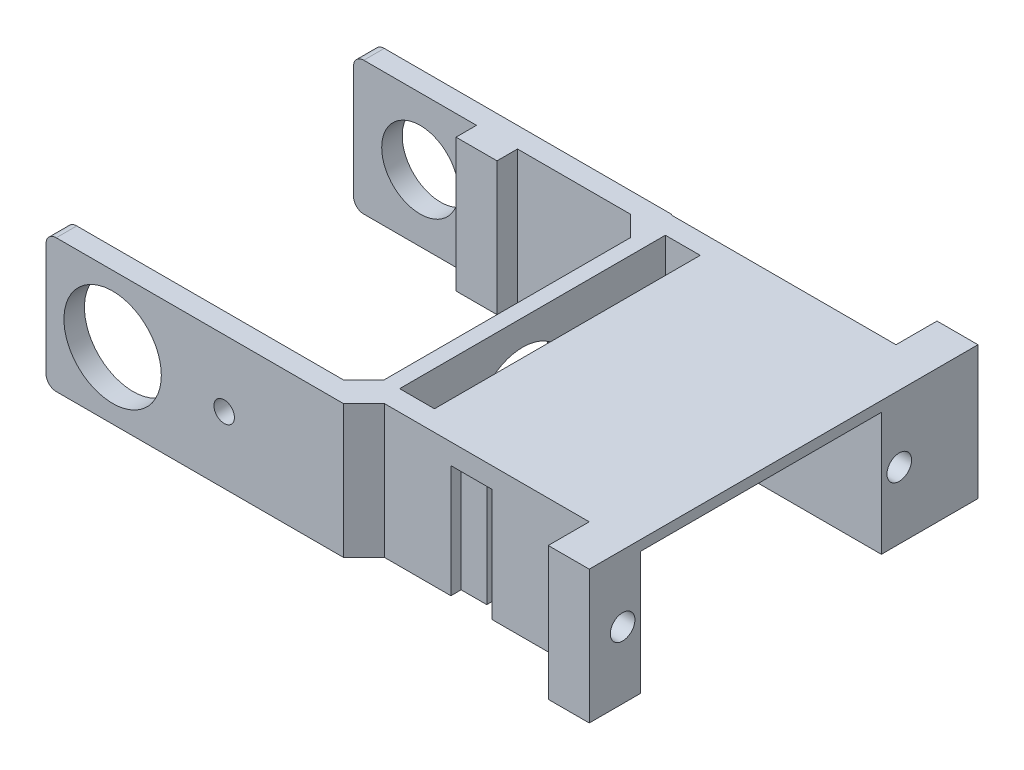
SolidWorks part; units mm, degrees
material "Plain Carbon Steel"
ref_plane "Front Plane" through (0, 0, 0) normal (0, 0, 1) x (1, 0, 0)
ref_plane "Top Plane" through (0, 0, 0) normal (0, 1, 0) x (1, 0, 0)
ref_plane "Right Plane" through (0, 0, 0) normal (1, 0, 0) x (0, 0, -1)
sketch "Sketch1" plane through (0, 0, 0) normal (0, 1, 0) x (1, 0, 0)
  line L0 (-0.069, 0) -> (0.0119, 0) construction
  line L13 (0, 70) -> (0, -70)
  line L14 (0, 70) -> (-10, 80)
  line L15 (-10, 80) -> (-155, 80)
  line L16 (-155, 80) -> (-155, 70)
  line L17 (-155, 70) -> (-20, 70)
  line L18 (-20, 70) -> (-10, 60)
  line L19 (-10, 60) -> (-10, -60)
  line L20 (-10, -60) -> (-20, -70)
  line L21 (-20, -70) -> (-155, -70)
  line L22 (0, -70) -> (-10, -80)
  line L23 (-10, -80) -> (-155, -80)
  line L24 (-155, -80) -> (-155, -70)
  point P6 (0, 0)
  dimension "D1" = 135
  dimension "D2" = 10
  dimension "D3" = 10
  dimension "D4" = 10
  dimension "D5" = 135
  dimension "D6" = 70
extrude "Boss-Extrude1" add sketch "Sketch1" along normal blind 65
fillet "Fillet1" radius 5 4 edges at (-155, 0, 75) (-155, 65, 75) (-155, 65, -75) (-155, 0, -75)
sketch "Sketch2" plane through (0, 0, 0) normal (0, 0, 1) x (1, 0, 0)
  line L0 (-150, 65) -> (-10, 65) construction
  line L1 (-155, 60) -> (-155, 5) construction
  circle A0 centre (-122.5, 32.5) radius 18.75
  dimension "D1" = 37.5
  dimension "D2" = 32.5
  dimension "D3" = 32.5
extrude "Cut-Extrude1" cut sketch "Sketch2" against normal up to surface (80 mm away) up to face at (-105.3452, 32.5, -80)
sketch "Sketch3" plane through (0, 0, 80) normal (0, 0, 1) x (1, 0, 0)
  line L0 (-155, 60) -> (-155, 5) construction
  line L1 (-150, 65) -> (-10, 65) construction
  circle A0 centre (-122.5, 32.5) radius 23.75
  dimension "D1" = 47.5
  dimension "D2" = 32.5
  dimension "D3" = 32.5
extrude "Cut-Extrude2" cut sketch "Sketch3" against normal up to surface (10 mm away) up to face at (-108.6785, 32.5, 70)
sketch "Sketch4" plane through (0, 0, 0) normal (0, 1, 0) x (1, 0, 0)
  line L0 (-9.6326, 79.6326) -> (120, 79.6326)
  line L1 (-10, 60) -> (-10, -60) construction
  line L4 (0, 70) -> (-10, 80) construction
  line L5 (120, 79.6326) -> (120, -70)
  line L6 (0, -70) -> (120, -70)
  line L7 (0, -70) -> (0, 70)
  line L8 (-9.6326, 79.6326) -> (0, 70)
  dimension "D1" = 130
  dimension "D2" = 149.6326
extrude "Boss-Extrude2" add sketch "Sketch4" along normal up to surface (65 mm away) contours L6 L5 L0 L8 L7 up to face at (-56.6667, 65, 0)
sketch "Sketch5" plane through (0, 0, 0) normal (0, -1, 0) x (1, 0, 0)
  line L0 (120, -4.8163) -> (-170.7058, -4.8163) construction
  line L1 (120, -79.6326) -> (120, 70) construction
  line L2 (-10, -60) -> (-10, 60) construction
  line L3 (-2.5, 60) -> (14.5, 60)
  line L4 (-2.5, 60) -> (-2.5, -69.6326)
  line L5 (-2.5, -69.6326) -> (14.5, -69.6326)
  line L6 (14.5, 60) -> (14.5, -69.6326)
  line L7 (-2.5, 60) -> (14.5, -69.6326) construction
  line L8 (-2.5, -69.6326) -> (14.5, 60) construction
  point P4 (6, -4.8163)
  dimension "D1" = 17
  dimension "D2" = 10
  dimension "D3" = 7.5
extrude "Cut-Extrude3" cut sketch "Sketch5" against normal up to surface (65 mm away) up to face at (-32.1166, 65, -1.3761)
sketch "Sketch6" plane through (0, 0, 0) normal (0, -1, 0) x (1, 0, 0)
  line L0 (0, 70) -> (120, 70) construction
  line L5 (120, -79.6326) -> (120, 70) construction
  line L6 (120, 65) -> (45, 65)
  line L7 (120, 65) -> (120, -52.5)
  line L8 (120, -52.5) -> (45, -52.5)
  line L9 (45, 65) -> (45, -52.5)
  dimension "D1" = 75
  dimension "D2" = 5
  dimension "D3" = 117.5
extrude "Cut-Extrude4" cut sketch "Sketch6" against normal blind 60
sketch "Sketch7" plane through (120, 0, 0) normal (1, 0, 0) x (0, 0, -1)
  line L0 (-80, 0) -> (-70, 0) construction
  line L1 (-70, 65) -> (-90, 65)
  line L2 (-70, 65) -> (-70, 0)
  line L3 (-70, 0) -> (-90, 0)
  line L4 (-90, 65) -> (-90, 0)
  line L5 (79.6326, 0) -> (52.5, 0) construction
  line L6 (79.6326, 65) -> (99.6326, 65)
  line L7 (79.6326, 65) -> (79.6326, 0)
  line L8 (79.6326, 0) -> (99.6326, 0)
  line L9 (99.6326, 65) -> (99.6326, 0)
  dimension "D1" = 20
  dimension "D2" = 20
extrude "Boss-Extrude3" add sketch "Sketch7" against normal blind 20
sketch "Sketch8" plane through (120, 0, 0) normal (1, 0, 0) x (0, 0, -1)
  line L3 (99.6326, 65) -> (-90, 65) construction
  line L4 (-6.25, 60) -> (-6.25, -23.4656) construction
  line L5 (52.5, 60) -> (-65, 60) construction
  circle A1 centre (-73.725, 32.5) radius 6
  circle A2 centre (61.225, 32.5) radius 6
  dimension "D1" = 12
  dimension "D4" = 12
  dimension "D5" = 134.95
  dimension "D6" = 32.5
extrude "Cut-Extrude6" cut sketch "Sketch8" against normal blind 20
sketch "Sketch9" plane through (0, 0, 70) normal (0, 0, 1) x (1, 0, 0)
  line L0 (0, 0) -> (100, 0) construction
  line L1 (32.5, 0) -> (52.5, 0)
  line L2 (32.5, 0) -> (32.5, 55)
  line L3 (32.5, 55) -> (52.5, 55)
  line L4 (52.5, 0) -> (52.5, 55)
  dimension "D1" = 20
  dimension "D2" = 55
  dimension "D3" = 32.5
extrude "Cut-Extrude8" cut sketch "Sketch9" against normal up to surface (5 mm away) up to face at (82.5, 30, 65)
sketch "Sketch10" plane through (-10, 0, 0) normal (-1, 0, 0) x (0, 0, 1)
  line L0 (-60, 0) -> (60, 0) construction
  line L1 (-60, 65) -> (-60, 0) construction
  circle A0 centre (0, 30) radius 22.5
  dimension "D1" = 45
  dimension "D2" = 30
  dimension "D3" = 60
extrude "Cut-Extrude9" cut sketch "Sketch10" against normal up to surface (7.5 mm away) up to face at (-2.5, 32.5, -4.8163)
sketch "Sketch11" plane through (0, 0, 0) normal (0, 1, 0) x (1, 0, 0)
  line L0 (-150, 70) -> (-20, 70) construction
  line L1 (-95, 70) -> (-75, 70)
  line L2 (-95, 70) -> (-95, 60)
  line L3 (-95, 60) -> (-75, 60)
  line L4 (-75, 70) -> (-75, 60)
  line L5 (-10, 60) -> (-10, -60) construction
  dimension "D1" = 20
  dimension "D2" = 10
  dimension "D3" = 85
extrude "Boss-Extrude4" add sketch "Sketch11" along normal up to surface (65 mm away) up to face at (6, 65, -4.8163)
sketch "Sketch12" plane through (0, 0, 80) normal (0, 0, 1) x (1, 0, 0)
  line L0 (-150, 65) -> (-10, 65) construction
  circle A0 centre (-68.08, 32.5) radius 5
  circle A1 centre (-122.5, 32.5) radius 23.75 construction
  dimension "D1" = 10
  dimension "D2" = 54.42
  dimension "D3" = 32.5
extrude "Cut-Extrude10" cut sketch "Sketch12" against normal up to surface (10 mm away) up to face at (-98.75, 32.5, 70)
